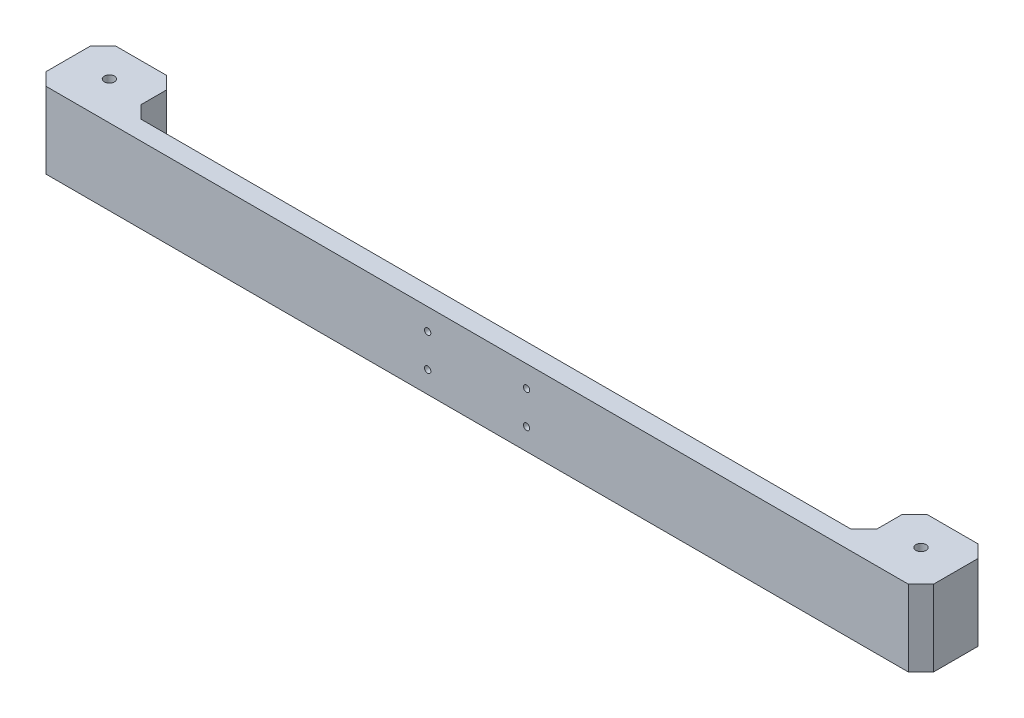
SolidWorks part; units mm, degrees
ref_plane "Front Plane" through (0, 0, 0) normal (0, 0, 1) x (1, 0, 0)
ref_plane "Top Plane" through (0, 0, 0) normal (0, 1, 0) x (1, 0, 0)
ref_plane "Right Plane" through (0, 0, 0) normal (1, 0, 0) x (0, 0, -1)
sketch "Sketch2" plane through (0, 0, 0) normal (0, 1, 0) x (1, 0, 0)
  line L0 (-350, -22.5) -> (350, -22.5) construction
  line L1 (-350, 5) -> (350, 5)
  line L2 (-350, 5) -> (-350, -50)
  line L3 (-350, -50) -> (350, -50)
  line L4 (350, 5) -> (350, -50)
  line L7 (-290, -35) -> (290, -35)
  line L8 (-290, -35) -> (-290, 5)
  line L9 (-290, 5) -> (290, 5)
  line L10 (290, -35) -> (290, 5)
  line L15 (0, 5) -> (0, -50) construction
  circle A0 centre (-320, -20) radius 4
  circle A1 centre (320, -20) radius 4
  point P0 (0, 0)
  point P12 (0, 5)
  dimension "D2" = 8
  dimension "D1" = 700
  dimension "D3" = 55
  dimension "D4" = 320
  dimension "D5" = 580
  dimension "D6" = 40
  dimension "D7" = 30
extrude "Boss-Extrude2" add sketch "Sketch2" along normal blind 60
chamfer "Chamfer3" distance 10 angle 45 8 edges at (350, 30, 50) (350, 30, -5) (290, 30, -5) (290, 30, 35) (-290, 30, 35) (-290, 30, -5) (-350, 30, 50) (-350, 30, -5)
sketch "Sketch3" plane through (0, 0, 50) normal (0, 0, 1) x (1, 0, 0)
  line L0 (-340, 30) -> (340, 30) construction
  line L1 (-340, 60) -> (-340, 0) construction
  line L2 (340, 0) -> (340, 60) construction
  line L3 (0, 0) -> (0, 60) construction
  line L4 (-340, 60) -> (340, 60) construction
  circle A0 centre (39, 43) radius 2.5
  circle A1 centre (39, 17) radius 2.5
  circle A2 centre (-39, 17) radius 2.5
  circle A3 centre (-39, 43) radius 2.5
  dimension "D1" = 5
  dimension "D2" = 13
  dimension "D3" = 39
extrude "Cut-Extrude1" cut sketch "Sketch3" against normal through all
